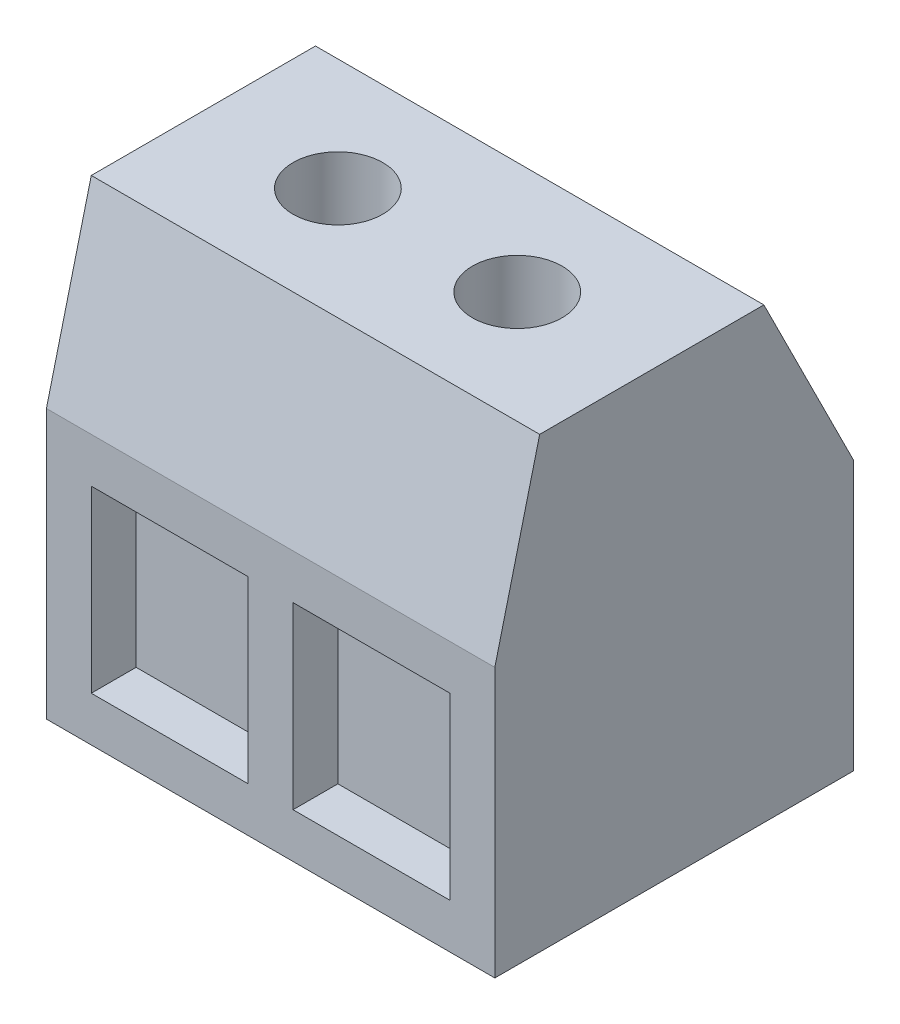
SolidWorks part; units mm, degrees
ref_plane "Front Plane" through (0, 0, 0) normal (0, 0, 1) x (1, 0, 0)
ref_plane "Top Plane" through (0, 0, 0) normal (0, 1, 0) x (1, 0, 0)
ref_plane "Right Plane" through (0, 0, 0) normal (1, 0, 0) x (0, 0, -1)
sketch "Sketch1" plane through (0, 0, 0) normal (0, 1, 0) x (1, 0, 0)
  line L1 (0, 0) -> (10, 0)
  line L2 (0, 0) -> (0, 8)
  line L3 (0, 8) -> (10, 8)
  line L4 (10, 0) -> (10, 8)
  dimension "D1" = 8
  dimension "D2" = 10
extrude "Boss-Extrude1" add sketch "Sketch1" along normal blind 10
sketch "Sketch3" plane through (10, 0, 0) normal (1, 0, 0) x (0, 0, -1)
  line L0 (0, 6) -> (1, 10)
  line L1 (0, 10) -> (0, 0) construction
  line L2 (0, 10) -> (8, 10) construction
  line L3 (1, 10) -> (6, 10)
  line L4 (6, 10) -> (8, 6)
  line L5 (8, 10) -> (8, 0) construction
  line L6 (8, 6) -> (9, 6)
  line L7 (9, 6) -> (9, 11)
  line L8 (9, 11) -> (-1, 11)
  line L9 (-1, 11) -> (-1, 6)
  line L10 (-1, 6) -> (0, 6)
  dimension "D1" = 1
  dimension "D2" = 1
  dimension "D3" = 1
  dimension "D4" = 4
  dimension "D5" = 4
  dimension "D6" = 1
  dimension "D7" = 2
extrude "Cut-Extrude1" cut sketch "Sketch3" against normal blind 10
sketch "Sketch4" plane through (0, 10, 0) normal (0, 1, 0) x (1, 0, 0)
  line L0 (3, 3.5) -> (7, 3.5) construction
  line L1 (5, 3.5) -> (5, 1) construction
  line L2 (0, 1) -> (10, 1) construction
  circle A0 centre (3, 3.5) radius 1
  circle A1 centre (7, 3.5) radius 1
  dimension "D1" = 2
  dimension "D2" = 2
  dimension "D3" = 4
  dimension "D4" = 2.5
extrude "Cut-Extrude2" cut sketch "Sketch4" against normal blind 2
sketch "Sketch5" plane through (0, 0, 0) normal (0, 0, 1) x (1, 0, 0)
  line L0 (0, 0) -> (10, 0) construction
  line L1 (1, 5) -> (4.5, 5)
  line L2 (1, 5) -> (1, 1)
  line L3 (1, 1) -> (4.5, 1)
  line L4 (4.5, 5) -> (4.5, 1)
  line L5 (5.5, 5) -> (9, 5)
  line L6 (5.5, 5) -> (5.5, 1)
  line L7 (5.5, 1) -> (9, 1)
  line L8 (9, 5) -> (9, 1)
  line L9 (0, 6) -> (0, 0) construction
  line L10 (10, 6) -> (10, 0) construction
  line L11 (0, 6) -> (10, 6) construction
  dimension "D1" = 1
  dimension "D2" = 1
  dimension "D3" = 1
  dimension "D4" = 1
  dimension "D5" = 1
  dimension "D6" = 1
  dimension "D7" = 1
  dimension "D8" = 3.5
  dimension "D9" = 3.5
extrude "Cut-Extrude3" cut sketch "Sketch5" against normal blind 1
